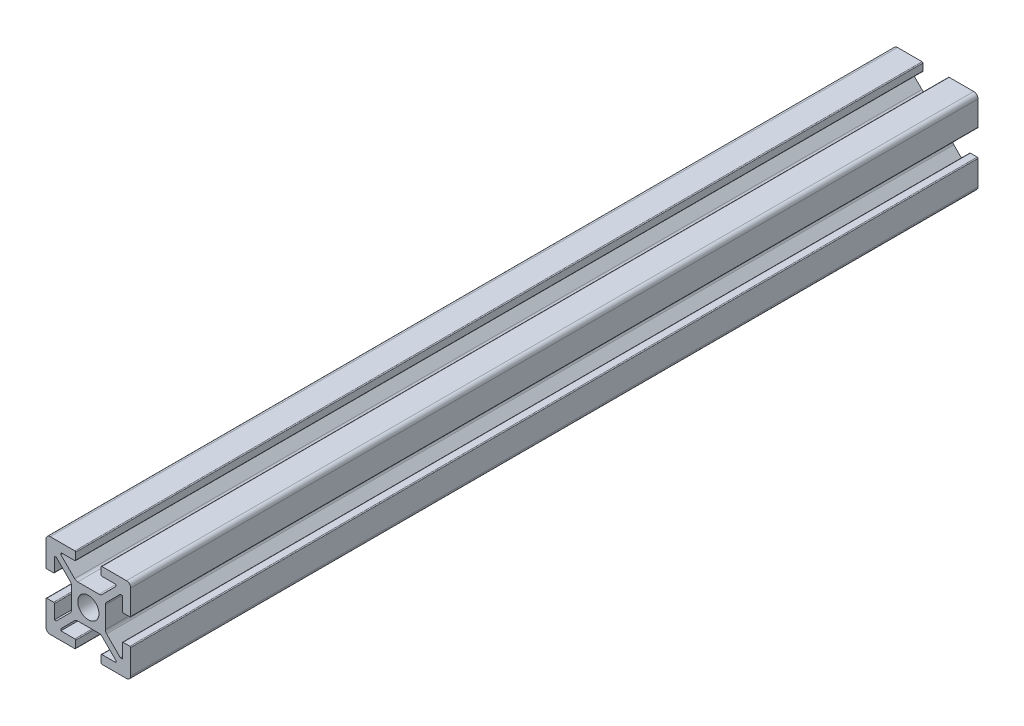
SolidWorks part; units mm, degrees
ref_plane "Front Plane" through (0, 0, 0) normal (0, 0, 1) x (1, 0, 0)
ref_plane "Top Plane" through (0, 0, 0) normal (0, 1, 0) x (1, 0, 0)
ref_plane "Right Plane" through (0, 0, 0) normal (1, 0, 0) x (0, 0, -1)
sketch "Sketch1" plane through (0, 0, 0) normal (0, 0, 1) x (1, 0, 0)
  line L0 (0.2, 13) -> (1.8, 13)
  line L1 (13.2, 0) -> (19, 0)
  line L2 (0, 13.2) -> (0, 19)
  line L3 (1, 20) -> (6.8, 20)
  line L4 (20, 1) -> (20, 6.8)
  line L5 (2, 13.2) -> (2, 16.5)
  line L6 (2, 16.5) -> (2.4393, 16.5)
  line L7 (2.4393, 16.5) -> (5.7071, 13.2322)
  line L8 (6, 12.5251) -> (6, 7.4749)
  line L11 (7.4749, 14) -> (10, 14)
  line L12 (3.5, 17.5607) -> (6.7678, 14.2929)
  line L13 (3.5, 18) -> (3.5, 17.5607)
  line L14 (6.8, 18) -> (3.5, 18)
  line L15 (6.8, 20) -> (1, 20)
  line L16 (7, 19.8) -> (7, 18.2)
  line L17 (19.8, 7) -> (18.2, 7)
  line L18 (20, 6.8) -> (20, 1)
  line L19 (18, 6.8) -> (18, 3.5)
  line L20 (18, 3.5) -> (17.5607, 3.5)
  line L21 (17.5607, 3.5) -> (14.2929, 6.7678)
  line L22 (14, 7.4749) -> (14, 12.5251)
  line L23 (12.5251, 6) -> (10, 6)
  line L24 (16.5, 2.4393) -> (13.2322, 5.7071)
  line L25 (16.5, 2) -> (16.5, 2.4393)
  line L26 (13.2, 2) -> (16.5, 2)
  line L27 (13.2, 0) -> (19, 0)
  line L28 (13, 0.2) -> (13, 1.8)
  line L30 (13, 19.8) -> (13, 18.2)
  line L31 (13.2, 20) -> (19, 20)
  line L32 (13.2, 18) -> (16.5, 18)
  line L33 (16.5, 18) -> (16.5, 17.5607)
  line L34 (16.5, 17.5607) -> (13.2322, 14.2929)
  line L35 (12.5251, 14) -> (10, 14)
  line L36 (17.5607, 16.5) -> (14.2929, 13.2322)
  line L37 (18, 16.5) -> (17.5607, 16.5)
  line L38 (18, 13.2) -> (18, 16.5)
  line L39 (20, 13.2) -> (20, 19)
  line L40 (19.8, 13) -> (18.2, 13)
  line L41 (7, 0.2) -> (7, 1.8)
  line L42 (6.8, 0) -> (1, 0)
  line L43 (6.8, 2) -> (3.5, 2)
  line L44 (3.5, 2) -> (3.5, 2.4393)
  line L45 (3.5, 2.4393) -> (6.7678, 5.7071)
  line L46 (7.4749, 6) -> (10, 6)
  line L47 (2.4393, 3.5) -> (5.7071, 6.7678)
  line L48 (2, 3.5) -> (2.4393, 3.5)
  line L49 (2, 6.8) -> (2, 3.5)
  line L50 (20, 19) -> (20, 13.2)
  line L51 (1, 0) -> (6.8, 0)
  line L52 (0, 6.8) -> (0, 1)
  line L53 (13.2, 20) -> (19, 20)
  line L54 (0.2, 7) -> (1.8, 7)
  arc A0 (20, 1) -> (19, 0) centre (19, 1) cw
  arc A1 (1, 0) -> (0, 1) centre (1, 1) cw
  arc A2 (0, 19) -> (1, 20) centre (1, 19) cw
  arc A3 (20, 19) -> (19, 20) centre (19, 19) ccw
  arc A4 (14.2929, 6.7678) -> (14, 7.4749) centre (15, 7.4749) cw
  arc A5 (12.5251, 6) -> (13.2322, 5.7071) centre (12.5251, 5) cw
  arc A6 (6.7678, 5.7071) -> (7.4749, 6) centre (7.4749, 5) cw
  arc A7 (5.7071, 6.7678) -> (6, 7.4749) centre (5, 7.4749) ccw
  arc A8 (14.2929, 13.2322) -> (14, 12.5251) centre (15, 12.5251) ccw
  arc A9 (13.2322, 14.2929) -> (12.5251, 14) centre (12.5251, 15) cw
  arc A10 (6, 12.5251) -> (5.7071, 13.2322) centre (5, 12.5251) ccw
  arc A11 (7.4749, 14) -> (6.7678, 14.2929) centre (7.4749, 15) cw
  arc A12 (0, 6.8) -> (0.2, 7) centre (0.2, 6.8) cw
  arc A13 (2, 6.8) -> (1.8, 7) centre (1.8, 6.8) ccw
  arc A14 (7, 1.8) -> (6.8, 2) centre (6.8, 1.8) ccw
  arc A15 (7, 0.2) -> (6.8, 0) centre (6.8, 0.2) cw
  arc A16 (13.2, 0) -> (13, 0.2) centre (13.2, 0.2) cw
  arc A17 (13.2, 2) -> (13, 1.8) centre (13.2, 1.8) ccw
  arc A18 (18.2, 7) -> (18, 6.8) centre (18.2, 6.8) ccw
  arc A19 (19.8, 7) -> (20, 6.8) centre (19.8, 6.8) cw
  arc A20 (20, 13.2) -> (19.8, 13) centre (19.8, 13.2) cw
  arc A21 (18, 13.2) -> (18.2, 13) centre (18.2, 13.2) ccw
  arc A22 (13, 19.8) -> (13.2, 20) centre (13.2, 19.8) cw
  arc A23 (13, 18.2) -> (13.2, 18) centre (13.2, 18.2) ccw
  arc A24 (6.8, 18) -> (7, 18.2) centre (6.8, 18.2) ccw
  arc A25 (7, 19.8) -> (6.8, 20) centre (6.8, 19.8) ccw
  arc A26 (1.8, 13) -> (2, 13.2) centre (1.8, 13.2) ccw
  arc A27 (0.2, 13) -> (0, 13.2) centre (0.2, 13.2) cw
  circle A28 centre (10, 10) radius 2.5
  point P19 (2, 13)
  dimension "D1" = 1
  dimension "D4" = 1
  dimension "D5" = 0.2
  dimension "D6" = 0.2
  dimension "D7" = 5
  dimension "D2" = 7
  dimension "D3" = 2
  dimension "D9" = 3.5
extrude "Boss-Extrude1" add sketch "Sketch1" along normal blind 200 contours A27 L0 A26 L5 L6 L7 A10 L8 A7 L47 L48 L49 A13 L54 A12 L52 A1 L42 A15 L41 A14 L43 L44 L45 A6 L46 L23 A5 L24 L25 L26 A17 L28 A16 L1 A0 L4 A19 L17 A18 L19 L20 L21 A4 L22 A8 L36 L37 L38 A21 L40
